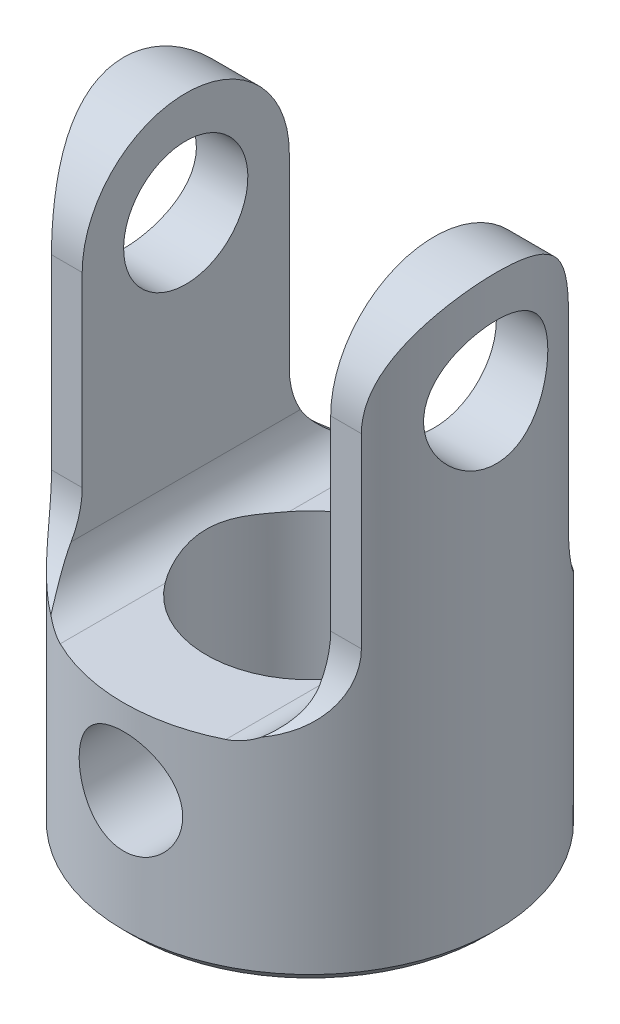
SolidWorks part; units mm, degrees
ref_plane "Front Plane" through (0, 0, 0) normal (0, 0, 1) x (1, 0, 0)
ref_plane "Top Plane" through (0, 0, 0) normal (0, 1, 0) x (1, 0, 0)
ref_plane "Right Plane" through (0, 0, 0) normal (1, 0, 0) x (0, 0, -1)
sketch "Sketch1" plane through (0, 0, 0) normal (0, 1, 0) x (1, 0, 0)
  circle A0 centre (0, 0) radius 4.5
  circle A1 centre (0, 0) radius 2.5
  dimension "D1" = 9
  dimension "D2" = 5
extrude "Boss-Extrude1" add sketch "Sketch1" along normal blind 14
sketch "Sketch2" plane through (0, 0, 0) normal (0, 0, 1) x (1, 0, 0)
  line L0 (4.5, 14) -> (-4.5, 14) construction
  line L1 (-3, 14) -> (3, 14)
  line L2 (-3, 14) -> (-3, 6)
  line L3 (-2, 5) -> (2, 5)
  line L4 (3, 14) -> (3, 6)
  line L5 (0, 3.15) -> (0, 0) construction
  line L7 (-4.5, 0) -> (4.5, 0) construction
  line L8 (-4.5, 14) -> (4.5, 14) construction
  arc A0 (2, 5) -> (3, 6) centre (2, 6) ccw
  arc A1 (-3, 6) -> (-2, 5) centre (-2, 6) ccw
  circle A2 centre (0, 3.15) radius 1.25
  point P16 (0, 14)
  point P17 (-2, 5)
  point P18 (0, 0)
  point P19 (0, 0)
  point P20 (0, 0)
  point P27 (3, 11.425)
  point P28 (2, 10.425)
  dimension "D3" = 1
  dimension "D4" = 2.5
  dimension "D5" = 4
  dimension "D1" = 6
  dimension "D2" = 3.15
  dimension "D6" = 8
extrude "Cut-Extrude1" cut sketch "Sketch2" against normal through all both and the other way through all
sketch "Sketch3" plane through (0, 0, 0) normal (1, 0, 0) x (0, 0, -1)
  line L0 (3.3541, 14) -> (-3.3541, 14) construction
  line L1 (2.5, 11.5) -> (2.5, 7)
  line L2 (-2.5, 11.5) -> (-2.5, 7)
  line L3 (0, 11.5) -> (0, 0) construction
  line L4 (4.5, 5) -> (4.5, 15)
  line L5 (4.5, 15) -> (-4.5, 15)
  line L6 (-4.5, 15) -> (-4.5, 5)
  line L9 (-4.5, 5) -> (4.5, 5) construction
  line L10 (4.5, 4.4) -> (4.5, 5) construction
  arc A0 (2.5, 11.5) -> (-2.5, 11.5) centre (0, 11.5) ccw
  arc A1 (-2.5, 7) -> (-4.5, 5) centre (-4.5, 7) cw
  arc A2 (2.5, 7) -> (4.5, 5) centre (4.5, 7) ccw
  circle A3 centre (0, 11.5) radius 1.5
  point P15 (0, 0)
  point P20 (-4.0825, 8.9559)
  dimension "D5" = 3
  dimension "D1" = 5
  dimension "D2" = 1
extrude "Cut-Extrude2" cut sketch "Sketch3" against normal through all both and the other way through all
chamfer "Chamfer1" distance 0.25 angle 45 1 edges at (0, 0, 4.5)
